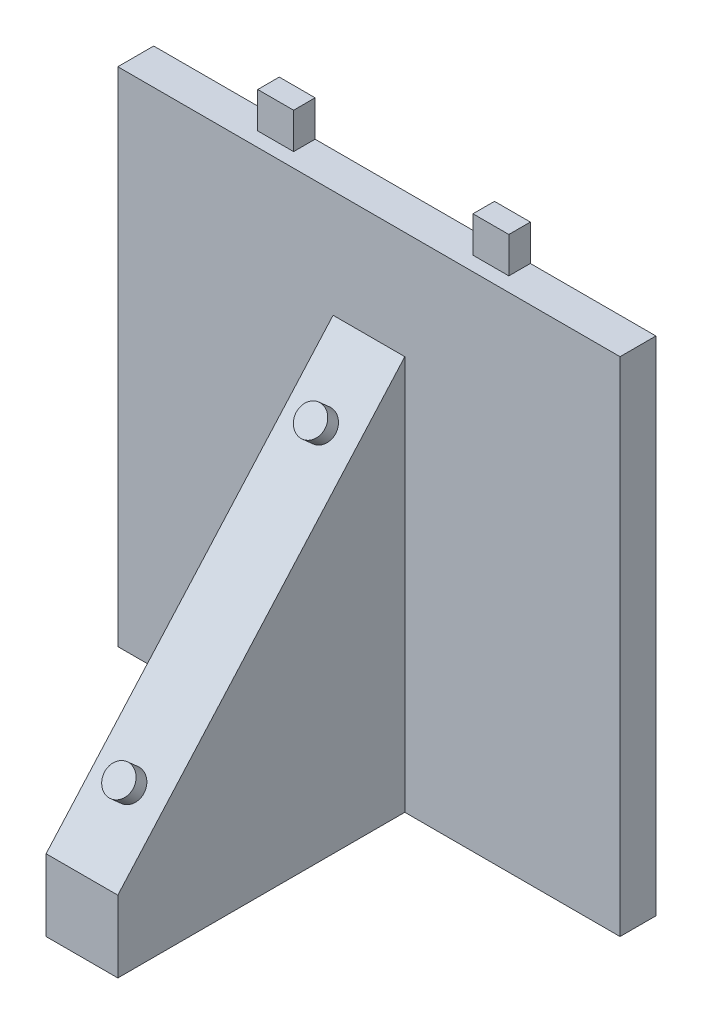
SolidWorks part; units mm, degrees
ref_plane "Front Plane" through (0, 0, 0) normal (1, 0, 0) x (0, 1, 0)
ref_plane "Top Plane" through (0, 0, 0) normal (0, 0, 1) x (0, 1, 0)
ref_plane "Right Plane" through (0, 0, 0) normal (0, 1, 0) x (-1, 0, 0)
sketch "Sketch1" plane through (0, 0, 0) normal (0, 0, 1) x (0, 1, 0)
  line L1 (-35, -35) -> (35, -35)
  line L2 (-35, -35) -> (-35, 35)
  line L3 (-35, 35) -> (35, 35)
  line L4 (35, -35) -> (35, 35)
  line L5 (-35, -35) -> (35, 35) construction
  line L6 (-35, 35) -> (35, -35) construction
  point P0 (0, 0)
  dimension "D1" = 70
  dimension "D2" = 70
extrude "Boss-Extrude1" add sketch "Sketch1" along normal blind 5
sketch "Sketch2" plane through (0, 35, 0) normal (0, 1, 0) x (-1, 0, 0)
  line L0 (-35, 5) -> (-35, 0) construction
  line L1 (-17.5, 0) -> (-12.5, 0)
  line L2 (-17.5, 0) -> (-17.5, 3)
  line L3 (-17.5, 3) -> (-12.5, 3)
  line L4 (-12.5, 0) -> (-12.5, 3)
  line L5 (-17.5, 0) -> (-12.5, 3) construction
  line L6 (-17.5, 3) -> (-12.5, 0) construction
  line L7 (-35, 0) -> (35, 0) construction
  line L8 (0, -1000) -> (0, 49000) construction
  line L9 (17.5, 3) -> (12.5, 0) construction
  line L10 (17.5, 0) -> (12.5, 3) construction
  line L11 (12.5, 0) -> (12.5, 3)
  line L12 (17.5, 3) -> (12.5, 3)
  line L13 (17.5, 0) -> (17.5, 3)
  line L14 (17.5, 0) -> (12.5, 0)
  point P0 (-15, 1.5)
  point P16 (15, 1.5)
  dimension "D1" = 20
  dimension "D2" = 5
  dimension "D3" = 3
extrude "Boss-Extrude2" add sketch "Sketch2" along normal blind 5
sketch "Sketch10" plane through (0, 0, 0) normal (1, 0, 0) x (0, 1, 0)
  line L0 (20, 5) -> (-25, 45)
  line L1 (-35, 5) -> (35, 5) construction
  line L2 (-25, 45) -> (-35, 45)
  line L3 (-35, 45) -> (-35, 5)
  line L4 (-35, 5) -> (20, 5)
  dimension "D1" = 10
  dimension "D2" = 40
  dimension "D3" = 20
extrude "Boss-Extrude6" add sketch "Sketch10" along normal blind 5 and the other way blind 5
sketch "Sketch16" plane through (0, 11.3103, 12.7241) normal (0, 0.6644, 0.7474) x (1, 0, 0)
  line L0 (-5, -48.5816) -> (5, -48.5816) construction
  line L1 (-5, 11.6264) -> (5, 11.6264) construction
  line L2 (-5, 11.6264) -> (-5, -48.5816) construction
  circle A0 centre (0, 1.6264) radius 2
  circle A1 centre (0, -38.5816) radius 2
  point P7 (0, -48.5816)
  dimension "D1" = 4
  dimension "D2" = 4
  dimension "D3" = 10
  dimension "D4" = 10
  dimension "D5" = 5
  dimension "D6" = 5
extrude "Boss-Extrude10" add sketch "Sketch16" along normal blind 2
